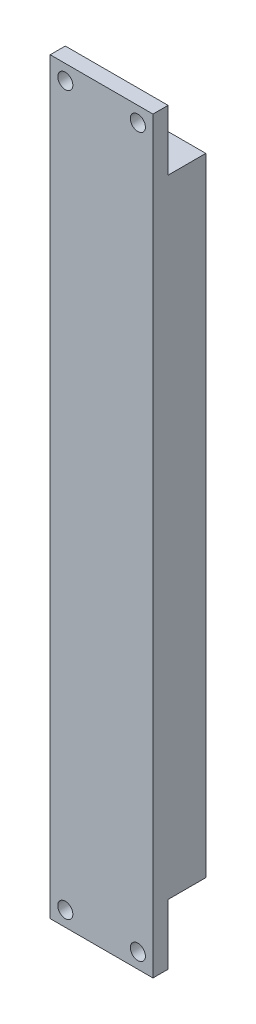
SolidWorks part; units mm, degrees
ref_plane "Front Plane" through (0, 0, 0) normal (0, 0, 1) x (1, 0, 0)
ref_plane "Top Plane" through (0, 0, 0) normal (0, 1, 0) x (1, 0, 0)
ref_plane "Right Plane" through (0, 0, 0) normal (1, 0, 0) x (0, 0, -1)
sketch "Sketch1" plane through (0, 0, 0) normal (0, 0, 1) x (1, 0, 0)
  line L1 (10.795, -78.5876) -> (-10.795, -78.5876)
  line L2 (10.795, -78.5876) -> (10.795, 78.5876)
  line L3 (10.795, 78.5876) -> (-10.795, 78.5876)
  line L4 (-10.795, -78.5876) -> (-10.795, 78.5876)
  line L5 (10.795, -78.5876) -> (-10.795, 78.5876) construction
  line L6 (10.795, 78.5876) -> (-10.795, -78.5876) construction
  point P0 (0, 0)
  dimension "D1" = 21.59
  dimension "D2" = 157.1752
extrude "Boss-Extrude1" add sketch "Sketch1" along normal blind 3.175
sketch "Sketch2" plane through (0, 0, 0) normal (0, 0, -1) x (-1, 0, 0)
  line L0 (-10.795, -78.5876) -> (-10.795, 78.5876) construction
  line L1 (-10.795, 65.8876) -> (10.795, 65.8876)
  line L2 (-10.795, 65.8876) -> (-10.795, -65.8876)
  line L3 (-10.795, -65.8876) -> (10.795, -65.8876)
  line L4 (10.795, 65.8876) -> (10.795, -65.8876)
  line L5 (10.795, 78.5876) -> (10.795, -78.5876) construction
  line L6 (10.795, -78.5876) -> (-10.795, -78.5876) construction
  line L7 (-10.795, 78.5876) -> (10.795, 78.5876) construction
  dimension "D1" = 12.7
  dimension "D2" = 12.7
extrude "Boss-Extrude2" add sketch "Sketch2" along normal blind 7.9248
sketch "Sketch3" plane through (0, 0, 3.175) normal (0, 0, 1) x (1, 0, 0)
  line L0 (-10.795, 78.5876) -> (-10.795, -78.5876) construction
  line L1 (10.795, 78.5876) -> (-10.795, 78.5876) construction
  line L2 (0, 0) -> (0, 104.2585) construction
  line L3 (0, 0) -> (58.1455, 0) construction
  circle A0 centre (-7.62, 75.4126) radius 1.5875
  circle A1 centre (7.62, 75.4126) radius 1.5875
  circle A2 centre (7.62, -75.4126) radius 1.5875
  circle A3 centre (-7.62, -75.4126) radius 1.5875
  dimension "D3" = 3.175
  dimension "D1" = 3.175
  dimension "D2" = 3.175
extrude "Cut-Extrude1" cut sketch "Sketch3" against normal blind 4.7752
